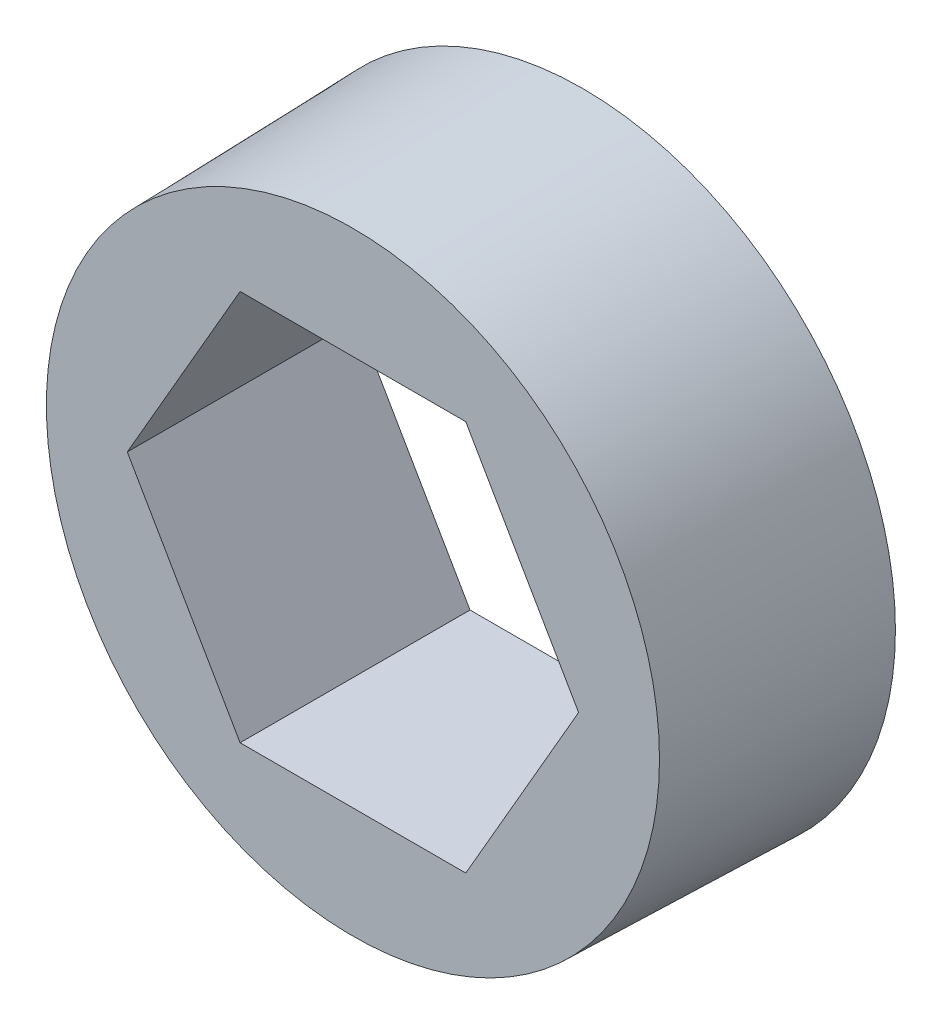
SolidWorks part; units mm, degrees
ref_plane "Front Plane" through (0, 0, 0) normal (0, 0, 1) x (1, 0, 0)
ref_plane "Top Plane" through (0, 0, 0) normal (0, 1, 0) x (1, 0, 0)
ref_plane "Right Plane" through (0, 0, 0) normal (1, 0, 0) x (0, 0, -1)
sketch "Sketch1" plane through (0, 0, 0) normal (0, 1, 0) x (1, 0, 0)
  line L0 (4.0786, 1.5) -> (0, 1.5)
  line L1 (0, 1.5) -> (0, -1.5)
  line L2 (0, -1.5) -> (4, -1.5)
  line L3 (4, -1.5) -> (4.0786, 1.5)
  line L4 (0, 1.5) -> (0, -1.5) construction
revolve "Revolve1" add sketch "Sketch1" angle 360 about L4
sketch "Sketch2" plane through (0, 0, -1.5) normal (0, 0, -1) x (-1, 0, 0)
  line L0 (-2.9445, 0) -> (-1.4722, -2.55)
  line L1 (-1.4722, -2.55) -> (1.4722, -2.55)
  line L2 (1.4722, -2.55) -> (2.9445, 0)
  line L3 (2.9445, 0) -> (1.4722, 2.55)
  line L4 (1.4722, 2.55) -> (-1.4722, 2.55)
  line L5 (-1.4722, 2.55) -> (-2.9445, 0)
extrude "Cut-Extrude1" cut sketch "Sketch2" against normal through all
